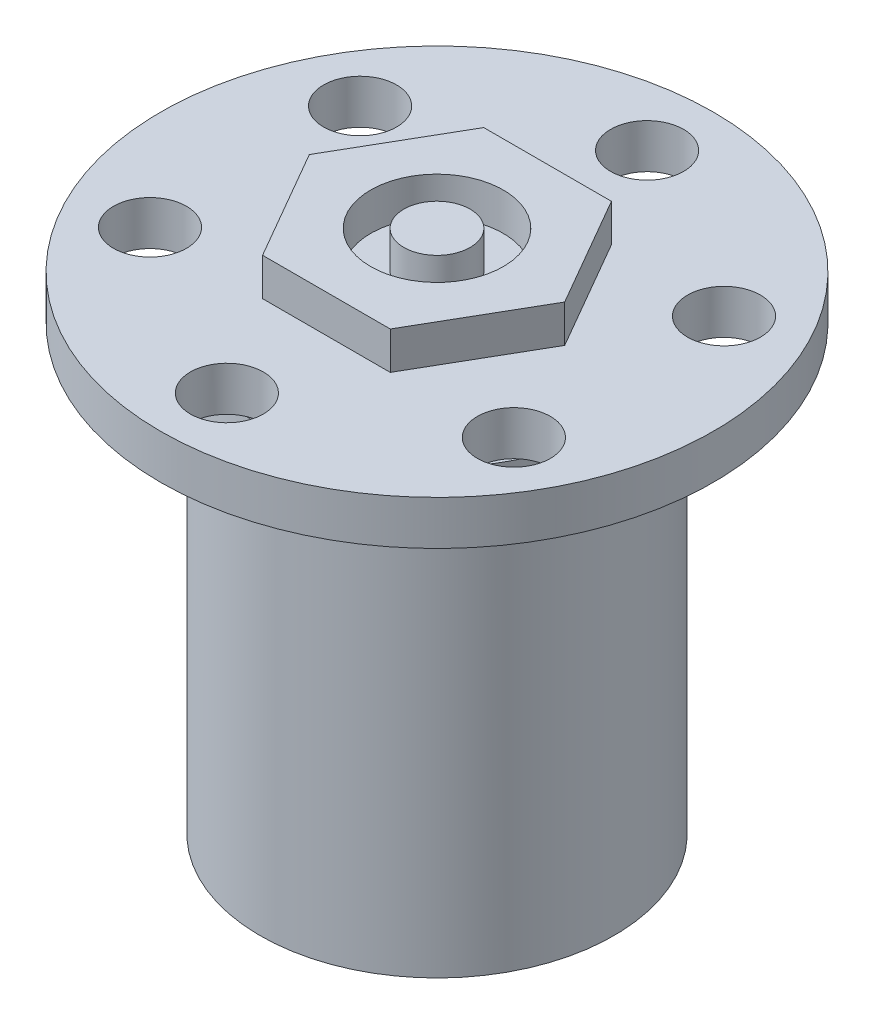
SolidWorks part; units mm, degrees
ref_plane "Спереди" through (0, 0, 0) normal (0, 0, 1) x (1, 0, 0)
ref_plane "Сверху" through (0, 0, 0) normal (0, 1, 0) x (1, 0, 0)
ref_plane "Справа" through (0, 0, 0) normal (1, 0, 0) x (0, 0, -1)
sketch "Эскиз1" plane through (0, 0, 0) normal (0, 1, 0) x (1, 0, 0)
  circle A0 centre (0, 0) radius 12.5
  dimension "D1" = 25
extrude "Бобышка-Вытянуть1" add sketch "Эскиз1" along normal blind 2
sketch "Эскиз2" plane through (0, 0, 0) normal (0, -1, 0) x (1, 0, 0)
  circle A0 centre (0, -9.5) radius 1.65
  circle A1 centre (0, 0) radius 9.5 construction
  dimension "D1" = 19
  dimension "D2" = 3.3
extrude "Вырез-Вытянуть1" cut sketch "Эскиз2" against normal through all
pattern_circular "Круговой массив1" count 6 over 360 about axis through (0, 0, 0) along (0, 1, 0) of "Вырез-Вытянуть1"
sketch "Эскиз3" plane through (0, 0, 0) normal (0, -1, 0) x (1, 0, 0)
  circle A0 centre (0, 0) radius 8
  dimension "D1" = 16
extrude "Бобышка-Вытянуть2" add sketch "Эскиз3" along normal blind 20
sketch "Эскиз4" plane through (0, 2, 0) normal (0, 1, 0) x (1, 0, 0)
  line L1 (-5.7735, 0) -> (-2.8868, -5)
  line L2 (-2.8868, -5) -> (2.8868, -5)
  line L3 (2.8868, -5) -> (5.7735, 0)
  line L4 (5.7735, 0) -> (2.8868, 5)
  line L5 (2.8868, 5) -> (-2.8868, 5)
  line L6 (-2.8868, 5) -> (-5.7735, 0)
  circle A0 centre (0, 0) radius 5 construction
  dimension "D1" = 10
extrude "Бобышка-Вытянуть3" add sketch "Эскиз4" along normal blind 1.7
sketch "Эскиз5" plane through (0, 3.7, 0) normal (0, 1, 0) x (1, 0, 0)
  circle A0 centre (0, 0) radius 3
  circle A1 centre (0, 0) radius 1.5
  dimension "D1" = 6
  dimension "D2" = 3
extrude "Вырез-Вытянуть2" cut sketch "Эскиз5" against normal up to surface (1.7 mm away) up to face at (0, 2, 0)
